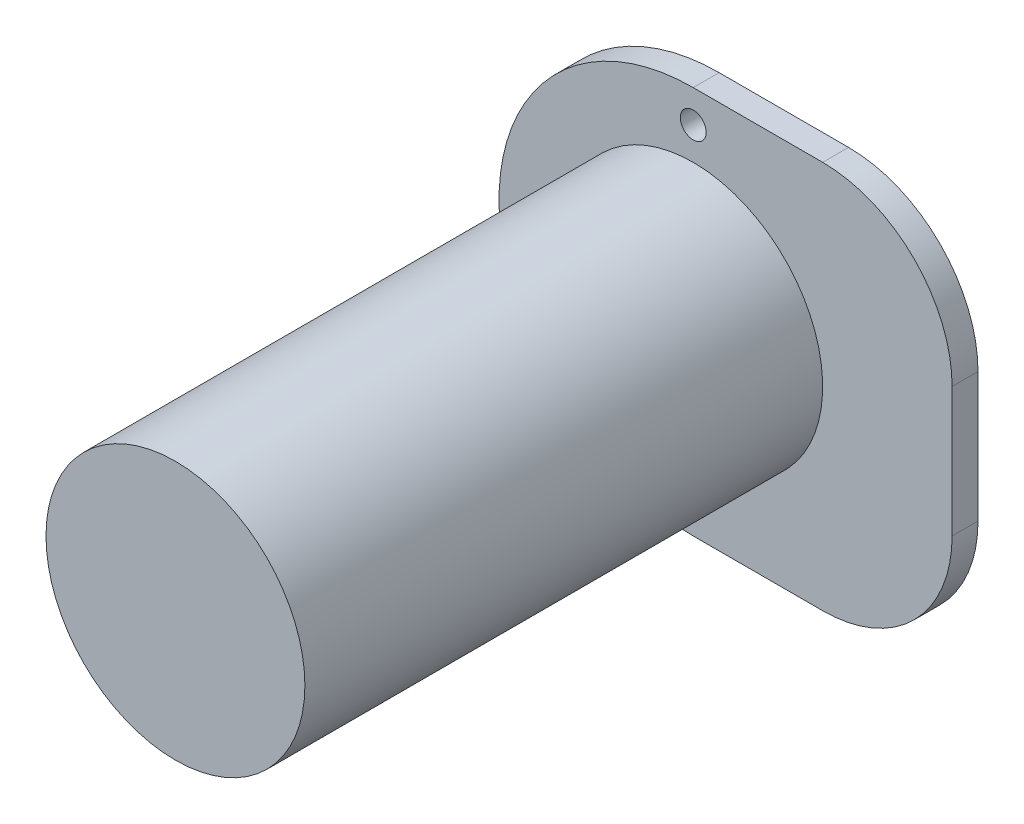
SolidWorks part; units mm, degrees
material "1060 Alloy"
ref_plane "Front" through (0, 0, 0) normal (0, 0, 1) x (1, 0, 0)
ref_plane "Top" through (0, 0, 0) normal (0, 1, 0) x (1, 0, 0)
ref_plane "Right" through (0, 0, 0) normal (1, 0, 0) x (0, 0, -1)
sketch "Sketch1" plane through (0, 0, 0) normal (0, 0, 1) x (1, 0, 0)
  line L0 (0, 75) -> (-100, 75)
  line L1 (-100, 75) -> (-100, -75)
  line L2 (-100, -75) -> (0, -75)
  arc A0 (0, -75) -> (0, 75) centre (0, 0) ccw
  circle A1 centre (0, 0) radius 50
  dimension "D1" = 150
  dimension "D3" = 100
  dimension "D2" = 100
extrude "Boss-Extrude1" add sketch "Sketch1" along normal mid plane 210 contours A1
sketch "Sketch2" plane through (0, 0, -105) normal (0, 0, -1) x (-1, 0, 0)
  line L0 (0, 75) -> (0, -75)
  line L1 (0, 75) -> (-100, 75)
  line L2 (-100, 75) -> (-100, -75)
  line L3 (-100, -75) -> (0, -75)
  arc A0 (0, -75) -> (0, 75) centre (0, 0) ccw
  point P5 (0, 0)
  circle M3 centre (0, 0) radius 50
  dimension "D1" = 150
  dimension "D2" = 100
extrude "Boss-Extrude3" add sketch "Sketch2" against normal blind 10 contours L0 A0 M3 | L2 L3 L0 L1 M3
sketch "Sketch3" plane through (0, 0, -105) normal (0, 0, -1) x (-1, 0, 0)
  circle A0 centre (0, 0) radius 62.5
  circle A1 centre (0, 62.5) radius 5
  circle A2 centre (62.5, 0) radius 5
  circle A3 centre (0, -62.5) radius 5
  point P12 (0, 0)
  dimension "D1" = 125
  dimension "D2" = 10
  dimension "D3" = 3
extrude "Cut-Extrude1" cut sketch "Sketch3" against normal blind 10 contours A1 | A2 | A3
fillet "Fillet1" radius 50 2 edges at (100, -75, -100) (100, 75, -100)
